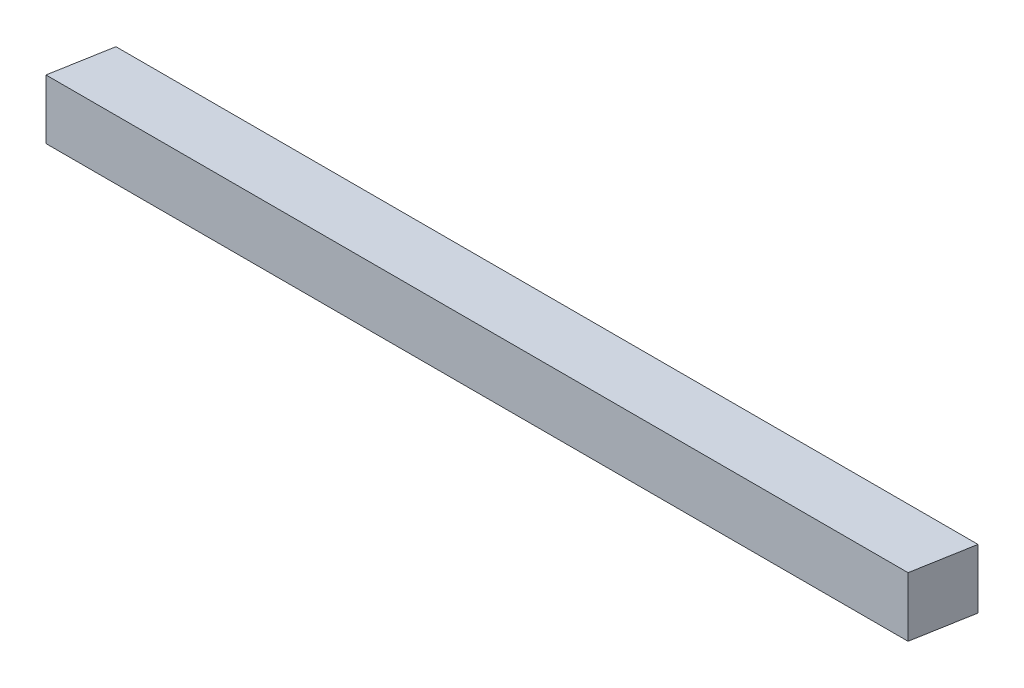
SolidWorks part; units mm, degrees
ref_plane "Front Plane" through (0, 0, 0) normal (0, 0, 1) x (1, 0, 0)
ref_plane "Top Plane" through (0, 0, 0) normal (0, 1, 0) x (1, 0, 0)
ref_plane "Right Plane" through (0, 0, 0) normal (1, 0, 0) x (0, 0, -1)
sketch "Sketch1" plane through (0, 0, 0) normal (0, 1, 0) x (1, 0, 0)
  line L0 (0, 0) -> (2.2394, 12.7)
  line L1 (2.2394, 12.7) -> (186.3894, 12.7)
  line L2 (186.3894, 12.7) -> (184.15, 0)
  line L3 (184.15, 0) -> (0, 0)
  dimension "D1" = 184.15
  dimension "D2" = 184.15
  dimension "D3" = 80
  dimension "D4" = 12.7
extrude "Boss-Extrude1" add sketch "Sketch1" along normal blind 12.7
